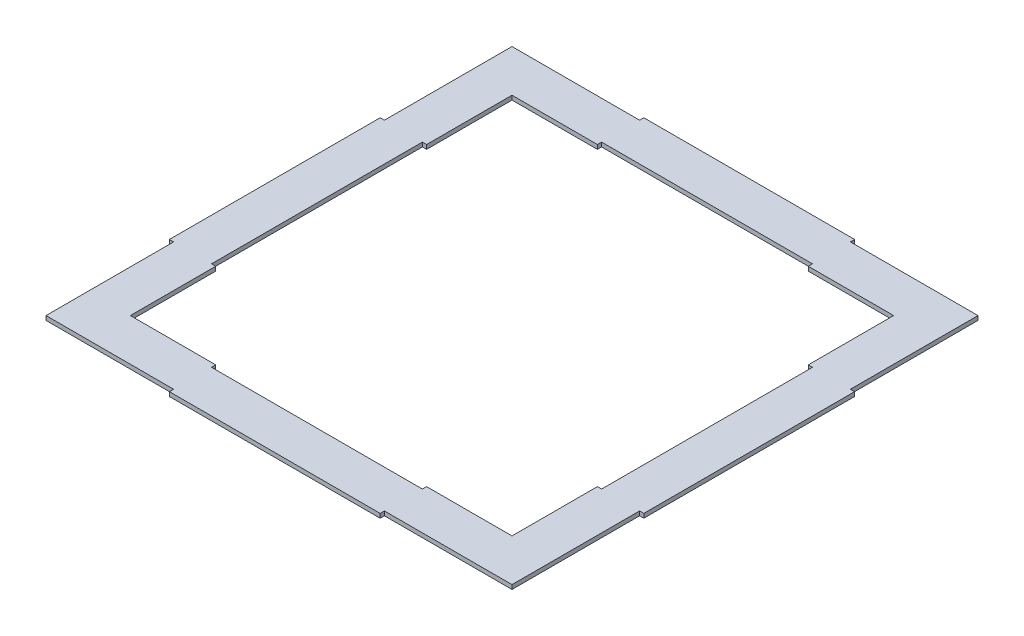
SolidWorks part; units mm, degrees
ref_plane "Front Plane" through (0, 0, 0) normal (0, 0, 1) x (1, 0, 0)
ref_plane "Top Plane" through (0, 0, 0) normal (0, 1, 0) x (1, 0, 0)
ref_plane "Right Plane" through (0, 0, 0) normal (1, 0, 0) x (0, 0, -1)
sketch "Sketch1" plane through (0, 0, 0) normal (0, 1, 0) x (1, 0, 0)
  line L0 (-219.3166, 100.4209) -> (-223.3166, 100.4209)
  line L1 (-223.3166, 100.4209) -> (-223.3166, -99.5791)
  line L2 (-223.3166, -99.5791) -> (-219.3166, -99.5791)
  line L3 (-219.3166, -99.5791) -> (-219.3166, -220.5791)
  line L4 (-219.3166, -220.5791) -> (-98.3166, -220.5791)
  line L5 (-98.3166, -220.5791) -> (-98.3166, -224.5791)
  line L6 (-98.3166, -224.5791) -> (101.6834, -224.5791)
  line L7 (101.6834, -224.5791) -> (101.6834, -220.5791)
  line L8 (101.6834, -220.5791) -> (222.6834, -220.5791)
  line L9 (222.6834, -220.5791) -> (222.6834, -99.5791)
  line L10 (222.6834, -99.5791) -> (226.6834, -99.5791)
  line L11 (226.6834, -99.5791) -> (226.6834, 100.4209)
  line L12 (226.6834, 100.4209) -> (222.6834, 100.4209)
  line L13 (222.6834, 100.4209) -> (222.6834, 221.4209)
  line L14 (222.6834, 221.4209) -> (101.6834, 221.4209)
  line L15 (101.6834, 221.4209) -> (101.6834, 225.4209)
  line L16 (101.6834, 225.4209) -> (-98.3166, 225.4209)
  line L17 (-98.3166, 225.4209) -> (-98.3166, 221.4209)
  line L18 (-98.3166, 221.4209) -> (-219.3166, 221.4209)
  line L19 (-219.3166, 221.4209) -> (-219.3166, 100.4209)
  line L20 (-179.3166, -180.5791) -> (-98.3166, -180.5791)
  line L21 (-179.3166, -180.5791) -> (-179.3166, -99.5791)
  line L22 (-179.3166, 181.4209) -> (-98.3166, 181.4209)
  line L23 (182.6834, -180.5791) -> (182.6834, -99.5791)
  line L24 (-179.3166, 100.4209) -> (-179.3166, 181.4209)
  line L25 (182.6834, 100.4209) -> (182.6834, 181.4209)
  line L26 (101.6834, 181.4209) -> (182.6834, 181.4209)
  line L28 (-98.3166, 181.4209) -> (-98.3166, 185.4209)
  line L29 (-98.3166, 185.4209) -> (101.6834, 185.4209)
  line L30 (101.6834, 181.4209) -> (101.6834, 185.4209)
  line L31 (-179.3166, 100.4209) -> (-183.3166, 100.4209)
  line L33 (-179.3166, -99.5791) -> (-183.3166, -99.5791)
  line L34 (-183.3166, 100.4209) -> (-183.3166, -99.5791)
  line L39 (182.6834, 100.4209) -> (186.6834, 100.4209)
  line L41 (182.6834, -99.5791) -> (186.6834, -99.5791)
  line L42 (186.6834, 100.4209) -> (186.6834, -99.5791)
  line L43 (101.6834, -180.5791) -> (182.6834, -180.5791)
  line L44 (-98.3166, -180.5791) -> (-98.3166, -184.5791)
  line L45 (-98.3166, -184.5791) -> (101.6834, -184.5791)
  line L46 (101.6834, -184.5791) -> (101.6834, -180.5791)
  point P20 (1.6834, 0.4209)
  point P21 (1.6834, 0.4209)
  dimension "D1" = 200
  dimension "D2" = 4
  dimension "D3" = 450
  dimension "D4" = 450
  dimension "D5" = 121
  dimension "D6" = 200
  dimension "D7" = 121
  dimension "D8" = 4
  dimension "D9" = 121
  dimension "D10" = 121
  dimension "D11" = 225
  dimension "D12" = 4
  dimension "D13" = 225
  dimension "D14" = 4
  dimension "D15" = 4
  dimension "D16" = 4
  dimension "D17" = 200
  dimension "D18" = 121
  dimension "D19" = 121
  dimension "D20" = 40
  dimension "D21" = 40
  dimension "D22" = 40
  dimension "D23" = 40
extrude "Boss-Extrude1" add sketch "Sketch1" along normal blind 4
